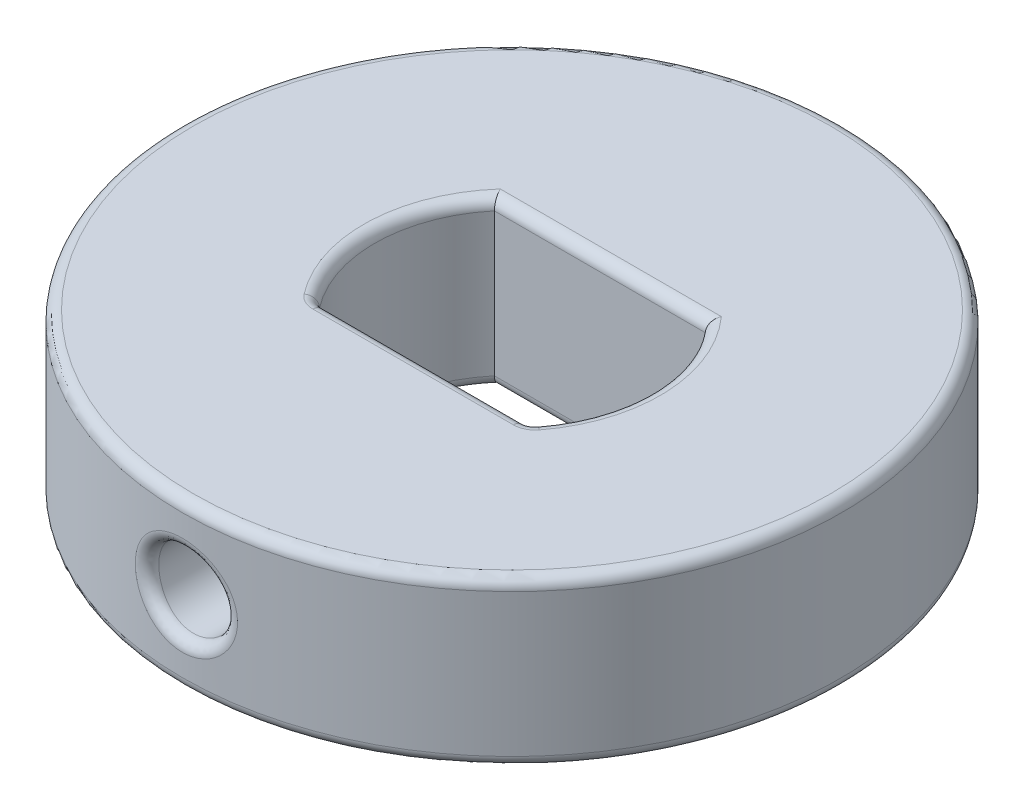
SolidWorks part; units mm, degrees
ref_plane "Front Plane" through (0, 0, 0) normal (0, 0, 1) x (1, 0, 0)
ref_plane "Top Plane" through (0, 0, 0) normal (0, 1, 0) x (1, 0, 0)
ref_plane "Right Plane" through (0, 0, 0) normal (1, 0, 0) x (0, 0, -1)
sketch "Sketch2" plane through (0, 0, 0) normal (0, 1, 0) x (1, 0, 0)
  line L5 (35.0915, -0.5) -> (44.6962, -0.5)
  line L6 (35.0915, -0.5) -> (25.4868, -0.5)
  line L8 (35.0915, 15.5) -> (25.4868, 15.5)
  line L9 (35.0915, 15.5) -> (44.6962, 15.5)
  arc A2 (25.4868, 15.5) -> (25.4868, -0.5) centre (35.0915, 7.5) ccw
  arc A3 (44.6962, -0.5) -> (44.6962, 15.5) centre (35.0915, 7.5) ccw
  circle A4 centre (35.0915, 7.5) radius 30
  dimension "D3" = 35.0915
  dimension "D6" = 8
  dimension "D8" = 12.5
  dimension "D5" = 9.6047
  dimension "D2" = 60
  dimension "D7" = 8
  dimension "D9" = 9.6047
  dimension "D10" = 35.884
extrude "Boss-Extrude1" add sketch "Sketch2" along normal blind 15
sketch "Sketch4" plane through (0, 0, 0) normal (0, 0, 1) x (1, 0, 0)
  line L3 (5.0915, 15) -> (5.0915, 0) construction
  circle A0 centre (35.0915, 7.5) radius 3.5
  dimension "D3" = 7
  dimension "D1" = 7.5
  dimension "D2" = 30
extrude "Cut-Extrude1" cut sketch "Sketch4" along normal blind 25
fillet "Fillet1" radius 1 14 edges at (38.5039, 8.2783, 22.3053) (22.5915, 0, -7.5) (35.0915, 0, -15.5) (47.5915, 0, -7.5) (35.0915, 0, 0.5) (35.0915, 0, 22.5) (35.0915, 15, -15.5) (22.5915, 15, -7.5) (35.0915, 15, 0.5) (47.5915, 15, -7.5) (35.0915, 15, 22.5) (44.6962, 7.5, 0.5) (25.4868, 7.5, 0.5) (31.5915, 7.5, 0.5)
